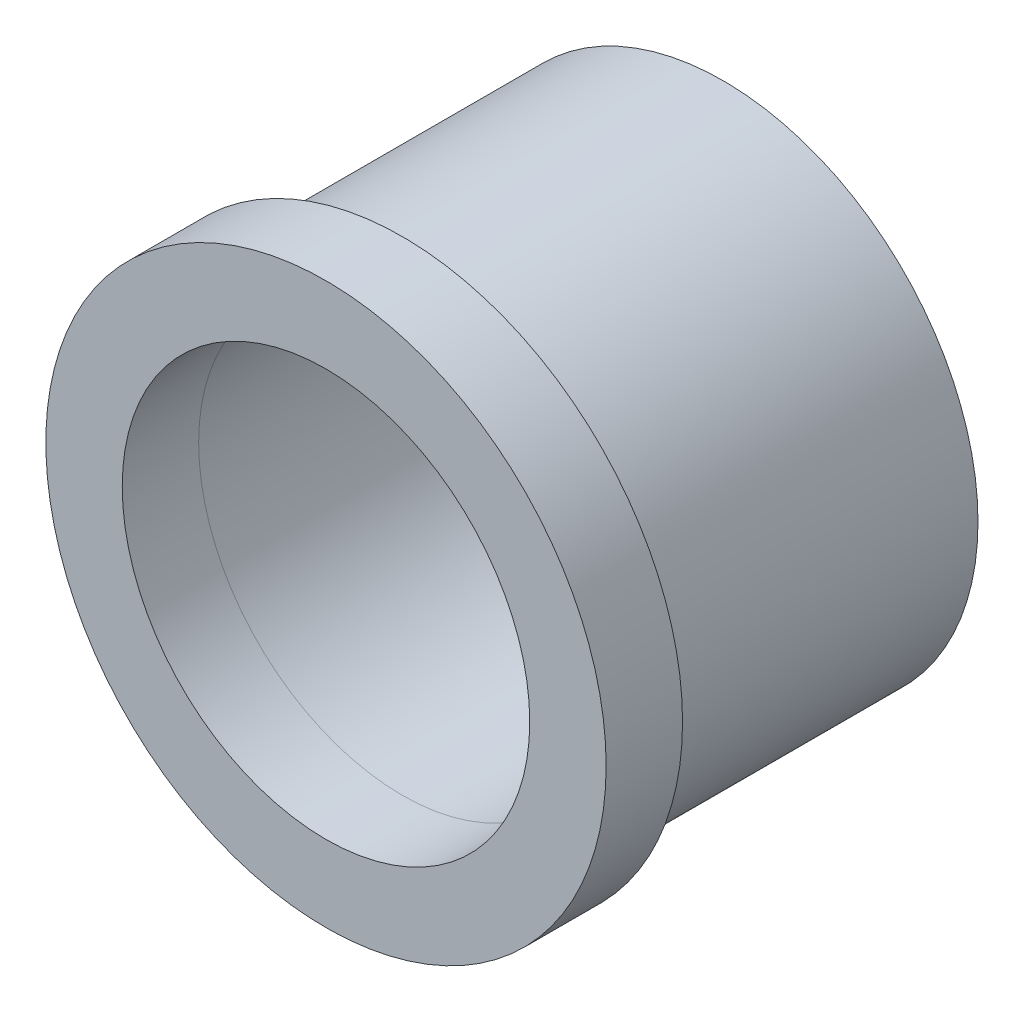
SolidWorks part; units mm, degrees
ref_plane "Plan de face" through (0, 0, 0) normal (0, 0, 1) x (1, 0, 0)
ref_plane "Plan de dessus" through (0, 0, 0) normal (0, 1, 0) x (1, 0, 0)
ref_plane "Plan de droite" through (0, 0, 0) normal (1, 0, 0) x (0, 0, -1)
sketch "Esquisse1" plane through (0, 0, 0) normal (0, 0, 1) x (1, 0, 0)
  circle A0 centre (0, 0) radius 4
  circle A1 centre (0, 0) radius 5
  dimension "D1" = 8
  dimension "D2" = 10
extrude "Boss.-Extru.1" add sketch "Esquisse1" along normal blind 6.3
sketch "Esquisse2" plane through (0, 0, 6.3) normal (0, 0, 1) x (1, 0, 0)
  circle A0 centre (0, 0) radius 5.5
  circle A3 centre (0, 0) radius 4 construction
  circle A4 centre (0, 0) radius 4
  dimension "D1" = 11
extrude "Boss.-Extru.2" add sketch "Esquisse2" along normal blind 1.5 separate body
